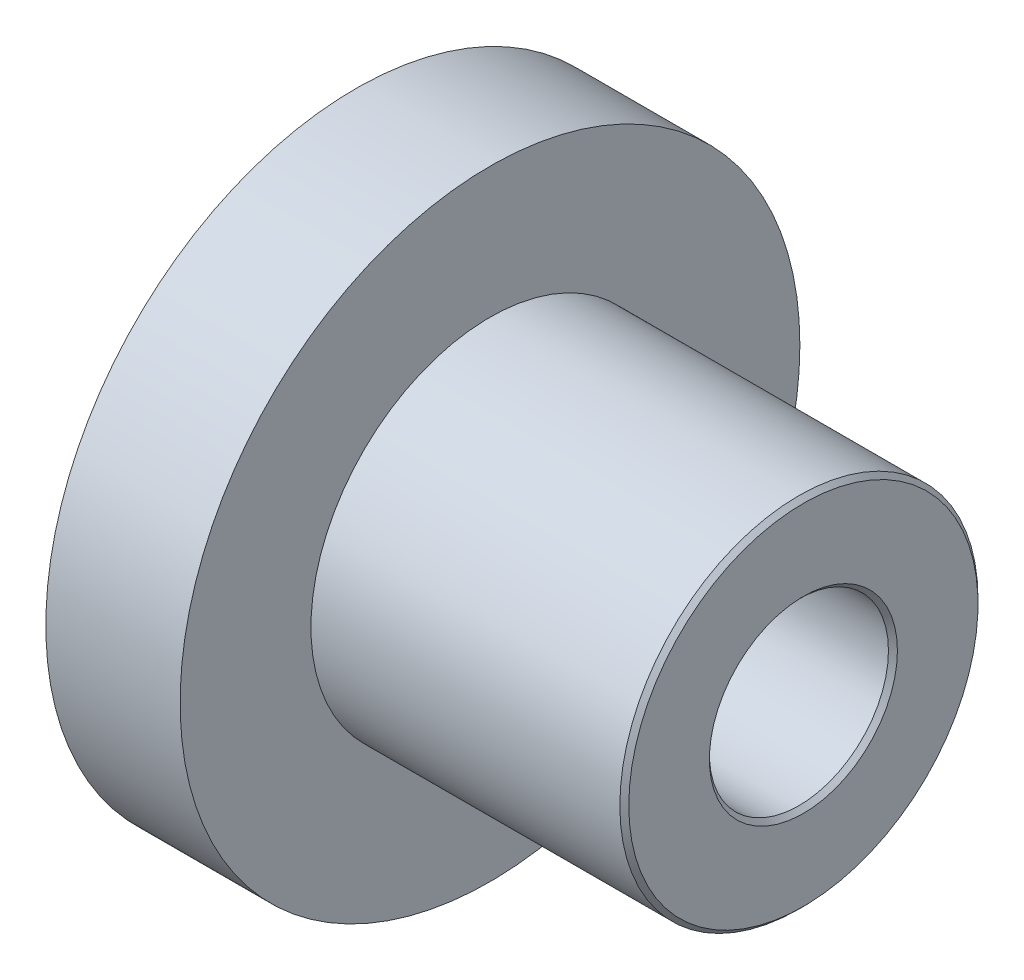
SolidWorks part; units mm, degrees
ref_plane "Front Plane" through (0, 0, 0) normal (0, 0, 1) x (1, 0, 0)
ref_plane "Top Plane" through (0, 0, 0) normal (0, 1, 0) x (1, 0, 0)
ref_plane "Right Plane" through (0, 0, 0) normal (1, 0, 0) x (0, 0, -1)
ref_plane "Plane1" through (1.5, 0, 0) normal (1, 0, 0) x (0, 0, -1)
sketch "Sketch1" plane through (1.5, 0, 0) normal (1, 0, 0) x (0, 0, -1)
  circle A1 centre (0, 0) radius 6.9215
  dimension "D1" = 6.9215
extrude "Boss-Extrude1" add sketch "Sketch1" against normal blind 3
sketch "Sketch3" plane through (0, 0, 0) normal (0, 0, 1) x (1, 0, 0)
  line L0 (1.5, 4) -> (1.5, 0)
  line L1 (1.5, 0) -> (8.5, 0)
  line L2 (8.5, 0) -> (8.5, 4)
  line L3 (8.5, 4) -> (1.5, 4)
  line L4 (1.5, 0) -> (8.5, 0) construction
  line L6 (1.5, -6.9215) -> (1.5, 6.9215) construction
  line L7 (1.5, -6.9215) -> (1.5, 6.9215) construction
  dimension "D1" = 4
  dimension "D2" = 7
revolve "Revolve1" add sketch "Sketch3" angle 360 about L4
hole_wizard "Ø4.0 (4) Diameter Hole1" positions "Sketch5" profile "Sketch4" hole size "Ø4.0" standard "ANSI Metric"
sketch "Sketch5" plane through (-1.5, 0, 0) normal (-1, 0, 0) x (0, 0, 1)
  point P0 (0, 0)
sketch "Sketch4" plane through (-1.5, 0, 0) normal (0, 1, 0) x (0, 0, 1)
  line L0 (0, 0) -> (0, 10)
  line L1 (0, 10) -> (2, 10)
  line L2 (2, 10) -> (2, 0)
  line L5 (2, 0) -> (0, 0)
  line L11 (0, -6.35) -> (0, 107.95) construction
  dimension "Thru Hole Dia." = 4
  dimension "Thru Hole Depth" = 10
chamfer "Chamfer1" distance 0.1 angle 45 3 edges at (8.5, 0, 2) (8.5, 0, -4) (-1.5, 0, 2)
